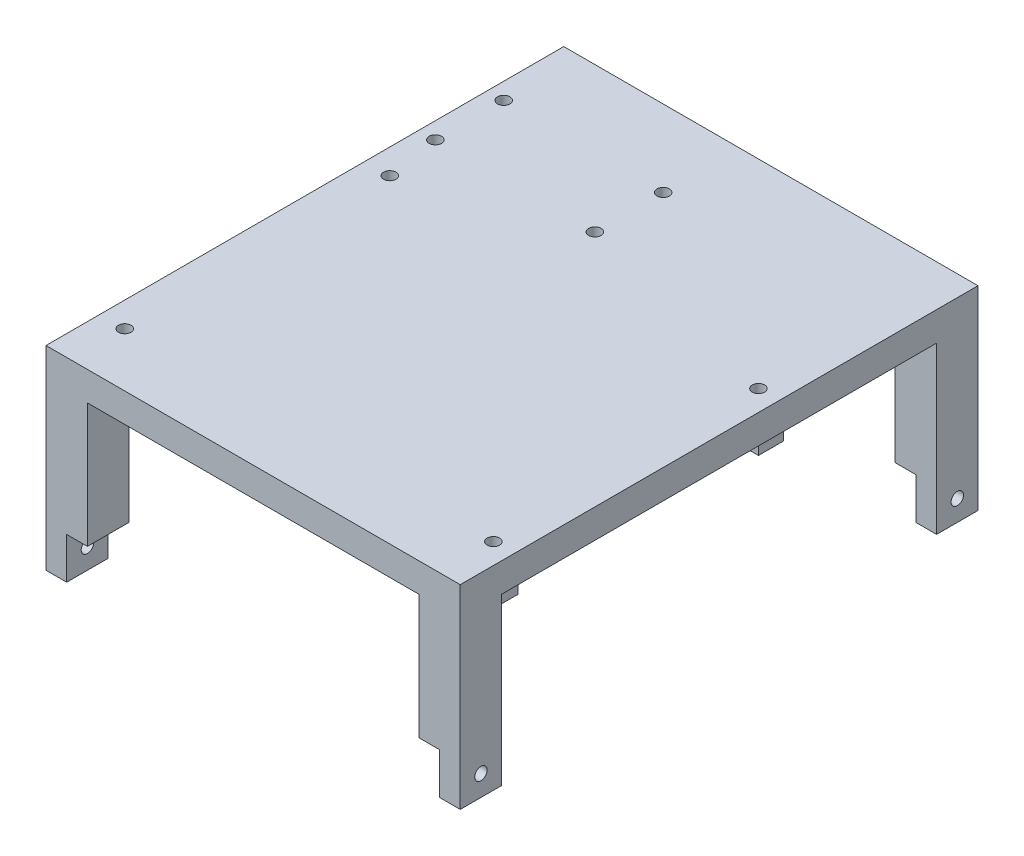
SolidWorks part; units mm, degrees
ref_plane "Front Plane" through (0, 0, 0) normal (0, 0, 1) x (1, 0, 0)
ref_plane "Top Plane" through (0, 0, 0) normal (0, 1, 0) x (1, 0, 0)
ref_plane "Right Plane" through (0, 0, 0) normal (1, 0, 0) x (0, 0, -1)
sketch "Sketch2" plane through (0, 0, 0) normal (0, 1, 0) x (1, 0, 0)
  line L1 (0, 0) -> (100, 0)
  line L2 (0, 0) -> (0, 80)
  line L3 (0, 80) -> (100, 80)
  line L4 (100, 0) -> (100, 80)
  dimension "D1" = 100
  dimension "D2" = 80
extrude "Boss-Extrude1" add sketch "Sketch2" along normal blind 10
sketch "Sketch3" plane through (0, 0, 0) normal (0, -1, 0) x (1, 0, 0)
  line L1 (100, 0) -> (90, 0)
  line L2 (100, 0) -> (100, -10)
  line L3 (100, -10) -> (90, -10)
  line L4 (90, 0) -> (90, -10)
  line L5 (0, 0) -> (10, 0)
  line L6 (0, 0) -> (0, -10)
  line L7 (0, -10) -> (10, -10)
  line L8 (10, 0) -> (10, -10)
  dimension "D1" = 10
  dimension "D2" = 10
extrude "Boss-Extrude2" add sketch "Sketch3" along normal blind 30
sketch "Sketch4" plane through (0, -30, 0) normal (0, -1, 0) x (1, 0, 0)
  line L0 (0, -10) -> (10, -10) construction
  line L1 (0, 0) -> (5, 0)
  line L2 (0, 0) -> (0, -10)
  line L3 (0, -10) -> (5, -10)
  line L4 (5, 0) -> (5, -10)
  line L5 (100, 0) -> (90, 0) construction
  line L6 (95, 0) -> (100, 0)
  line L7 (95, 0) -> (95, -10)
  line L8 (95, -10) -> (100, -10)
  line L9 (100, 0) -> (100, -10)
  line L10 (90, -10) -> (100, -10) construction
  line L11 (100, -10) -> (100, 0) construction
extrude "Boss-Extrude3" add sketch "Sketch4" along normal blind 10
sketch "Sketch5" plane through (0, 0, 0) normal (0, -1, 0) x (1, 0, 0)
  line L1 (3, -10) -> (9, -10)
  line L2 (3, -10) -> (3, -16)
  line L3 (3, -16) -> (9, -16)
  line L4 (9, -10) -> (9, -16)
  line L5 (98, -10) -> (92, -10)
  line L6 (98, -10) -> (98, -16)
  line L7 (98, -16) -> (92, -16)
  line L8 (92, -10) -> (92, -16)
  line L9 (98, -80) -> (92, -80)
  line L10 (98, -80) -> (98, -74)
  line L11 (98, -74) -> (92, -74)
  line L12 (92, -80) -> (92, -74)
  line L14 (3, -74) -> (9, -74)
  line L15 (3, -74) -> (3, -80)
  line L16 (3, -80) -> (9, -80)
  line L17 (9, -74) -> (9, -80)
  line L18 (100, -10) -> (100, -80) construction
  line L19 (100, -80) -> (0, -80) construction
  dimension "D1" = 6
  dimension "D2" = 70
  dimension "D3" = 95
  dimension "D4" = 2
extrude "Boss-Extrude4" add sketch "Sketch5" along normal blind 4
sketch "Sketch6" plane through (0, -4, 0) normal (0, -1, 0) x (1, 0, 0)
  line L0 (98, -16) -> (98, -10) construction
  line L1 (92, -16) -> (98, -16) construction
  line L2 (3, -74) -> (3, -80) construction
  line L3 (3, -80) -> (9, -80) construction
  circle A0 centre (6, -13) radius 1.5
  circle A1 centre (95, -13) radius 1.5
  circle A2 centre (95, -77) radius 1.5
  circle A3 centre (6, -77) radius 1.5
  point P8 (98, -13)
  dimension "D1" = 3
  dimension "D2" = 3
  dimension "D3" = 3
  dimension "D4" = 3
  dimension "D5" = 3
extrude "Cut-Extrude1" cut sketch "Sketch6" against normal through all
sketch "Sketch7" plane through (0, 0, -80) normal (0, 0, -1) x (-1, 0, 0)
  line L1 (0, 0) -> (-100, 0)
  line L2 (0, 0) -> (0, 10)
  line L3 (0, 10) -> (-100, 10)
  line L4 (-100, 0) -> (-100, 10)
extrude "Boss-Extrude5" add sketch "Sketch7" along normal blind 45
sketch "Sketch8" plane through (0, 0, 0) normal (0, -1, 0) x (1, 0, 0)
  line L1 (0, -125) -> (10, -125)
  line L2 (0, -125) -> (0, -115)
  line L3 (0, -115) -> (10, -115)
  line L4 (10, -125) -> (10, -115)
  line L5 (100, -125) -> (90, -125)
  line L6 (100, -125) -> (100, -115)
  line L7 (100, -115) -> (90, -115)
  line L8 (90, -125) -> (90, -115)
  dimension "D1" = 10
  dimension "D2" = 10
extrude "Boss-Extrude6" add sketch "Sketch8" along normal blind 30
sketch "Sketch9" plane through (0, -30, 0) normal (0, -1, 0) x (1, 0, 0)
  line L0 (0, -125) -> (10, -125) construction
  line L1 (0, -115) -> (5, -115)
  line L2 (0, -115) -> (0, -125)
  line L3 (0, -125) -> (5, -125)
  line L4 (5, -115) -> (5, -125)
  line L5 (90, -125) -> (100, -125) construction
  line L6 (100, -115) -> (95, -115)
  line L7 (100, -115) -> (100, -125)
  line L8 (100, -125) -> (95, -125)
  line L9 (95, -115) -> (95, -125)
extrude "Boss-Extrude7" add sketch "Sketch9" along normal blind 10
sketch "Sketch10" plane through (0, 0, 0) normal (-1, 0, 0) x (0, 0, 1)
  line L0 (0, -40) -> (-10, -40) construction
  line L1 (0, -30) -> (0, 0) construction
  line L2 (-125, -40) -> (-125, 10) construction
  circle A0 centre (-5, -35) radius 1.5
  circle A1 centre (-120, -35) radius 1.5
  dimension "D1" = 3
  dimension "D2" = 5
  dimension "D3" = 5
  dimension "D4" = 5
extrude "Cut-Extrude2" cut sketch "Sketch10" against normal through all
sketch "Sketch11" plane through (0, 0, 0) normal (0, -1, 0) x (1, 0, 0)
  line L0 (0, -115) -> (0, -10) construction
  line L1 (9, -80) -> (3, -80) construction
  circle A0 centre (4, -106.5) radius 1.5
  circle A1 centre (4, -90) radius 1.5
  circle A2 centre (42.5, -106.5) radius 1.5
  circle A3 centre (42.5, -90) radius 1.5
  dimension "D4" = 3
  dimension "D5" = 10
  dimension "D1" = 16.5
  dimension "D2" = 38.5
  dimension "D3" = 4
extrude "Cut-Extrude3" cut sketch "Sketch11" against normal up to surface (10 mm away) up to face at (6, 10, -78.5)
sketch "Sketch12" plane through (100, 0, 0) normal (1, 0, 0) x (0, 0, -1)
  line L1 (125, 10) -> (0, 10)
  line L2 (125, 10) -> (125, 7)
  line L3 (125, 7) -> (0, 7)
  line L4 (0, 10) -> (0, 7)
  dimension "D1" = 3
extrude "Cut-Extrude4" cut sketch "Sketch12" against normal up to surface (100 mm away) up to face at (0, -35, -118.5)
